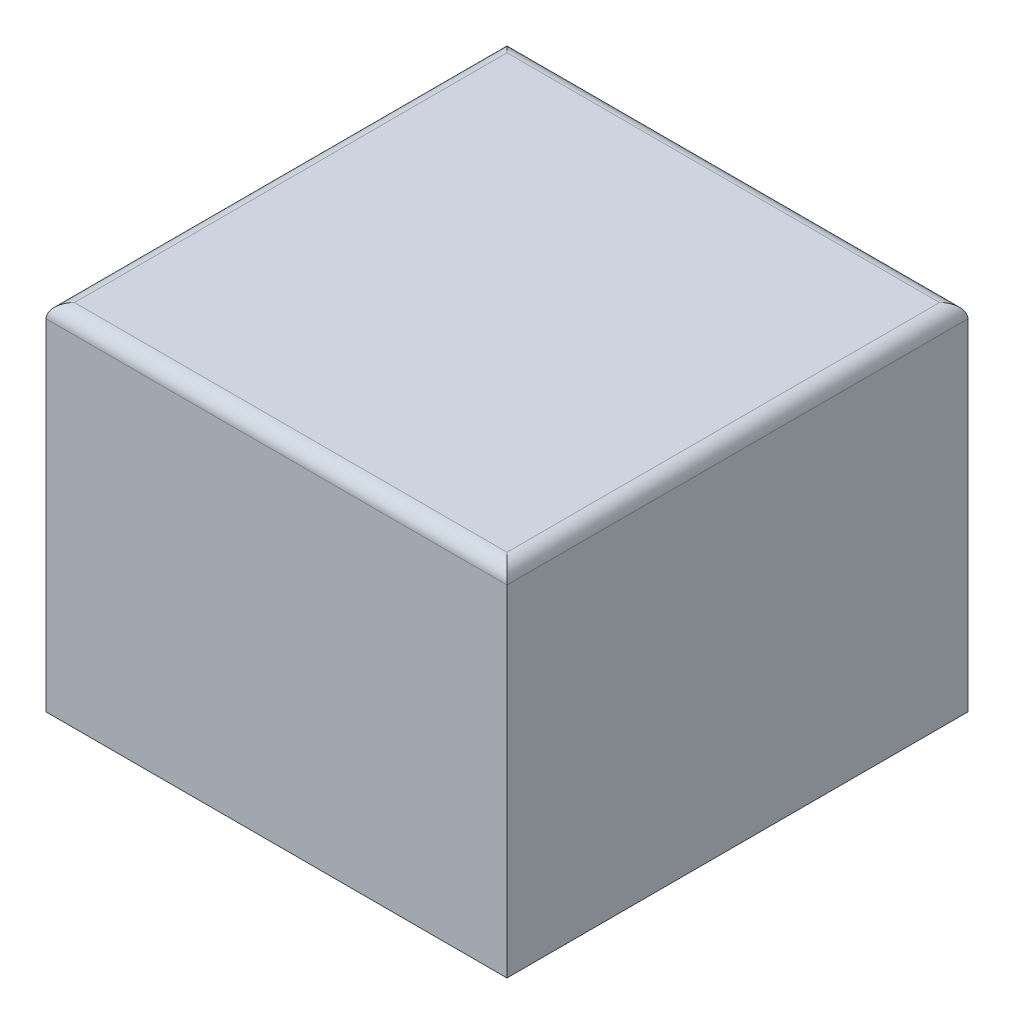
SolidWorks part; units mm, degrees
ref_plane "Front Plane" through (0, 0, 0) normal (0, 0, 1) x (1, 0, 0)
ref_plane "Top Plane" through (0, 0, 0) normal (0, 1, 0) x (1, 0, 0)
ref_plane "Right Plane" through (0, 0, 0) normal (1, 0, 0) x (0, 0, -1)
ref_plane "LowerPlane" through (0, 1, 0) normal (0, 1, 0) x (1, 0, 0)
ref_plane "MidPlane" through (0, 8, 0) normal (0, 1, 0) x (1, 0, 0)
ref_plane "TopPlane" through (0, 19.6, 0) normal (0, 1, 0) x (1, 0, 0)
sketch "Sketch1" plane through (0, 0, 0) normal (0, 1, 0) x (1, 0, 0)
  line L1 (-4, 7.2141) -> (-4, 12.2)
  line L2 (4, 7.2141) -> (4, 12.2)
  line L3 (-13, 13) -> (13, 13)
  line L4 (-13, 13) -> (-13, -13)
  line L5 (-13, -13) -> (13, -13)
  line L6 (13, 13) -> (13, -13)
  line L7 (7.2141, 4) -> (12.2, 4)
  line L8 (7.2141, -4) -> (12.2, -4)
  line L10 (-4, -12.2) -> (4, -12.2)
  line L15 (-4, -12.2) -> (-4, -7.2141)
  line L16 (-4, 12.2) -> (4, 12.2)
  line L28 (4, -12.2) -> (4, -7.2141)
  line L31 (-12.2, -4) -> (-7.2141, -4)
  line L32 (-12.2, -4) -> (-12.2, 4)
  line L33 (-12.2, 4) -> (-7.2141, 4)
  line L34 (12.2, -4) -> (12.2, 4)
  arc A0 (-7.2141, -4) -> (-4, -7.2141) centre (-6.5, -6.5) ccw
  arc A1 (-7.2141, 4) -> (-4, 7.2141) centre (-6.5, 6.5) cw
  arc A2 (7.2141, -4) -> (4, -7.2141) centre (6.5, -6.5) cw
  arc A3 (7.2141, 4) -> (4, 7.2141) centre (6.5, 6.5) ccw
  point P0 (0, 0)
  point P3 (0, 0)
  point P4 (0, 0)
  point P12 (0, 0)
  point P21 (0, 0)
  point P30 (0, 0)
  point P36 (0, 0)
extrude "Boss-Extrude1" add sketch "Sketch1" along normal up to surface (8 mm away) from surface at 0 up to plane "MidPlane" starting at plane "Top Plane"
sketch "Sketch22" plane through (0, 8, 0) normal (0, 1, 0) x (1, 0, 0)
  line L1 (-12.2, -12.2) -> (12.2, -12.2)
  line L2 (-12.2, -12.2) -> (-12.2, 12.2)
  line L3 (-12.2, 12.2) -> (12.2, 12.2)
  line L4 (12.2, -12.2) -> (12.2, 12.2)
  line L5 (-12.2, -12.2) -> (12.2, 12.2) construction
  line L6 (-12.2, 12.2) -> (12.2, -12.2) construction
  point P0 (0, 0)
  point P1 (0, 0)
sketch "Sketch21" plane through (0, 1, 0) normal (0, 1, 0) x (1, 0, 0)
  line L0 (-12.2, -12.2) -> (12.2, 12.2) construction
  line L3 (-7.5, -7.5) -> (7.5, -7.5)
  line L4 (-7.5, -7.5) -> (-7.5, 7.5)
  line L5 (-7.5, 7.5) -> (7.5, 7.5)
  line L6 (7.5, -7.5) -> (7.5, 7.5)
  line L7 (-7.5, -7.5) -> (7.5, 7.5) construction
  line L8 (-7.5, 7.5) -> (7.5, -7.5) construction
  point P0 (0, 0)
  point P1 (0, 0)
  point P2 (0, 0)
loft "Cut-Loft5" cut profiles "Sketch21", "Sketch22"
sketch "Sketch24" plane through (0, 8, 0) normal (0, 1, 0) x (1, 0, 0)
  line L1 (-13, 13) -> (13, 13)
  line L2 (-13, 13) -> (-13, -13)
  line L3 (-13, -13) -> (13, -13)
  line L4 (13, 13) -> (13, -13)
  line L5 (-13, 13) -> (13, -13) construction
  line L6 (-13, -13) -> (13, 13) construction
  line L7 (-12.2, 12.2) -> (12.2, 12.2)
  line L8 (-12.2, 12.2) -> (-12.2, -12.2)
  line L9 (-12.2, -12.2) -> (12.2, -12.2)
  line L10 (12.2, 12.2) -> (12.2, -12.2)
  line L11 (-12.2, 12.2) -> (12.2, -12.2) construction
  line L12 (-12.2, -12.2) -> (12.2, 12.2) construction
  point P0 (0, 0)
  point P6 (0, 0)
extrude "Boss-Extrude5" add sketch "Sketch24" along normal up to surface (11.6 mm away) up to plane "TopPlane"
sketch "Sketch27" plane through (0, 19.6, 0) normal (0, 1, 0) x (1, 0, 0)
  line L1 (-13, 13) -> (13, 13)
  line L2 (-13, 13) -> (-13, -13)
  line L3 (-13, -13) -> (13, -13)
  line L4 (13, 13) -> (13, -13)
  line L5 (-13, 13) -> (13, -13) construction
  line L6 (-13, -13) -> (13, 13) construction
  point P0 (0, 0)
extrude "Boss-Extrude7" add sketch "Sketch27" along normal blind 0.4
fillet "Fillet2" radius 0.8 4 edges at (0, 20, 13) (-13, 20, 0) (0, 20, -13) (13, 20, 0)
